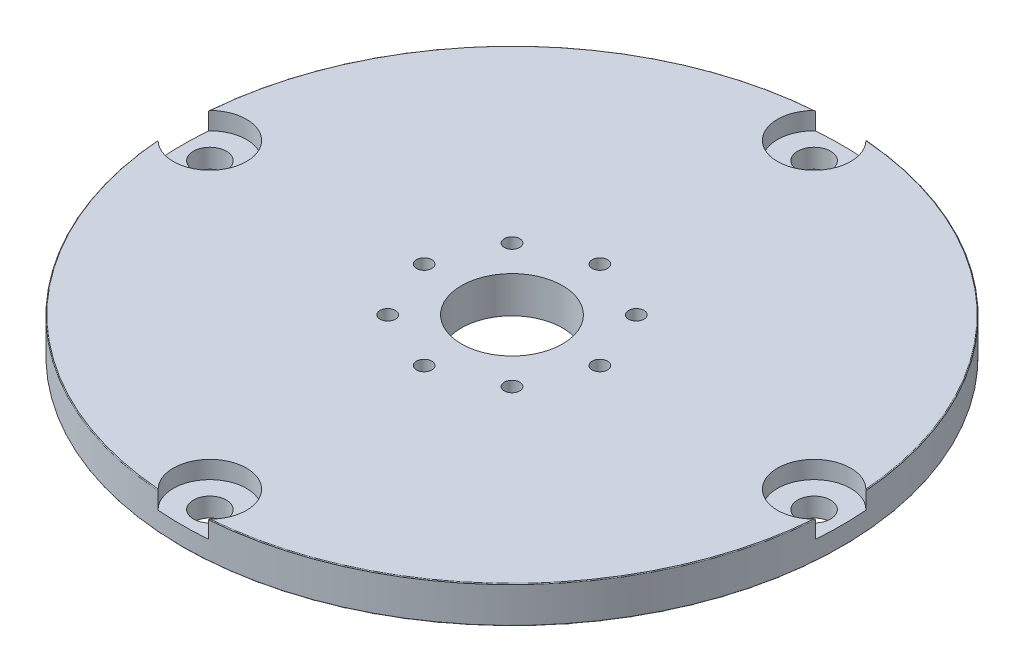
SolidWorks part; units mm, degrees
ref_plane "Plan de face" through (0, 0, 0) normal (0, 0, 1) x (1, 0, 0)
ref_plane "Plan de dessus" through (0, 0, 0) normal (0, 1, 0) x (1, 0, 0)
ref_plane "Plan de droite" through (0, 0, 0) normal (1, 0, 0) x (0, 0, -1)
sketch "Esquisse2" plane through (0, 0, 0) normal (0, 1, 0) x (1, 0, 0)
  circle A0 centre (0, 0) radius 45
  circle A1 centre (0, 0) radius 1.55
  dimension "D1" = 90
  dimension "D2" = 3.1
extrude "Boss.-Extru.1" add sketch "Esquisse2" along normal blind 6.5
sketch "Esquisse3" plane through (0, 6.5, 0) normal (0, 1, 0) x (1, 0, 0)
  circle A0 centre (0, 0) radius 6
  circle A1 centre (0, 0) radius 45
  circle A2 centre (0, 0) radius 45 construction
  dimension "D1" = 12
extrude "Enlèv. mat.-Extru.1" cut sketch "Esquisse3" against normal blind 1.5
fillet "Congé1" radius 0.1 5 edges at (0, 0, 45) (0, 5, 45) (0, 5, 6) (0, 6.5, 6) (0, 6.5, 1.55)
sketch "Esquisse5" plane through (0, 0, 0) normal (0, -1, 0) x (1, 0, 0)
  circle A0 centre (0, 0) radius 4
  dimension "D1" = 8
extrude "Enlèv. mat.-Extru.3" cut sketch "Esquisse5" against normal blind 5.5
sketch "Esquisse6" plane through (0, 0, 0) normal (0, -1, 0) x (1, 0, 0)
  line L0 (0, 0) -> (0, 10.3519) construction
  line L1 (0, 0) -> (8.7625, 0) construction
  line L2 (1.1, 8.7062) -> (1.1, 6.4062)
  line L3 (6.4062, 1.1) -> (8.7062, 1.1)
  arc A0 (1.1, 6.4062) -> (6.4062, 1.1) centre (0, 0) cw
  arc A1 (1.1, 8.7062) -> (8.7062, 1.1) centre (0, 0) cw
  dimension "D3" = 6.5
  dimension "D1" = 2.2
  dimension "D2" = 1.1
  dimension "D4" = 2.3
extrude "Enlèv. mat.-Extru.4" [suppressed] cut sketch "Esquisse6" against normal blind 2.5
fillet "Congé2" [suppressed] radius 0.25
pattern_circular "Répétition circulaire2" [suppressed] count 4 over 360
sketch "Esquisse7" plane through (0, 0, 0) normal (0, -1, 0) x (1, 0, 0)
  line L0 (0, 0) -> (0, 5.3406) construction
  line L1 (0, 5.3406) -> (-2.3501, 4) construction
  line L2 (-2.3501, 4) -> (2.3948, 4) construction
  line L5 (0.3, 4) -> (-0.3, 4)
  line L6 (-0.3, 4) -> (-0.1392, 3.4)
  line L7 (-0.1392, 3.4) -> (0.1392, 3.4)
  line L8 (0.1392, 3.4) -> (0.3, 4)
  circle A0 centre (0, 0) radius 4 construction
  dimension "D1" = 0.6
  dimension "D2" = 15
  dimension "D3" = 0.6
extrude "Boss.-Extru.2" [suppressed] add sketch "Esquisse7" against normal up to surface (5.5 mm away)
pattern_circular "Répétition circulaire3" [suppressed] count 24 over 360
sketch "Sketch1" plane through (0, 5, 0) normal (0, 1, 0) x (1, 0, 0)
  line L0 (-75.37, 0) -> (80.8545, 0) construction
  line L1 (0, 84.194) -> (0, -127.8325) construction
  circle A0 centre (0, 41.25) radius 2.25
  circle A1 centre (41.25, 0) radius 2.25
  circle A2 centre (0, -41.25) radius 2.25
  circle A3 centre (-41.25, 0) radius 2.25
  dimension "D2" = 4.5
  dimension "D4" = 4.5
  dimension "D1" = 41.25
  dimension "D3" = 41.25
extrude "Cut-Extrude1" cut sketch "Sketch1" against normal through all
sketch "Sketch2" plane through (0, 0, 0) normal (0, -1, 0) x (1, 0, 0)
  circle A0 centre (0, 12) radius 1.05
  dimension "D2" = 2.1
  dimension "D1" = 12
extrude "Cut-Extrude2" cut sketch "Sketch2" against normal through all
pattern_circular "CirPattern1" count 8 over 360 about axis through (0, 0, 0) along (0, 1, 0) of "Cut-Extrude2"
sketch "Sketch6" plane through (0, 6.5, 0) normal (0, 1, 0) x (1, 0, 0)
  circle A0 centre (0, 0) radius 6.9
  dimension "D1" = 13.8
extrude "Cut-Extrude3" cut sketch "Sketch6" along a picked direction on the side against the normal blind 10
sketch "Sketch7" plane through (0, 5, 0) normal (0, 1, 0) x (1, 0, 0)
  circle A0 centre (-41.25, 0) radius 5
  circle A1 centre (0, 41.25) radius 5
  circle A2 centre (41.25, 0) radius 5
  circle A3 centre (0, -41.25) radius 5
  dimension "D1" = 10
  dimension "D2" = 10
  dimension "D3" = 10
  dimension "D4" = 10
extrude "Cut-Extrude4" cut sketch "Sketch7" against normal blind 2.4
